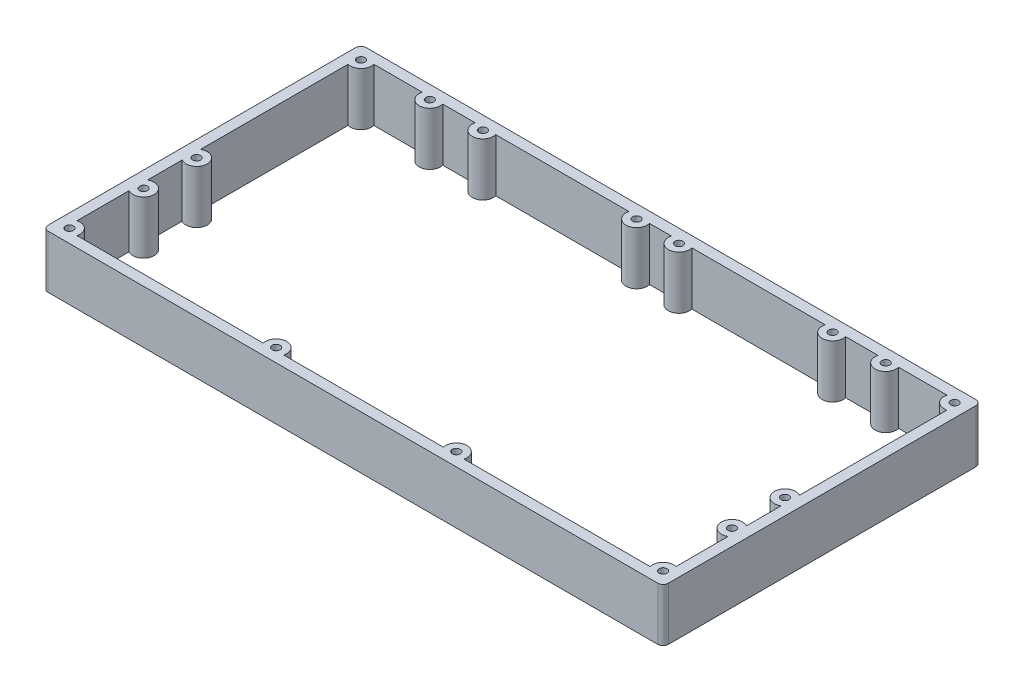
SolidWorks part; units mm, degrees
ref_plane "前视基准面" through (0, 0, 0) normal (0, 0, 1) x (1, 0, 0)
ref_plane "上视基准面" through (0, 0, 0) normal (0, 1, 0) x (1, 0, 0)
ref_plane "右视基准面" through (0, 0, 0) normal (1, 0, 0) x (0, 0, -1)
sketch "草图1" plane through (0, 0, 0) normal (0, 1, 0) x (1, 0, 0)
  line L0 (-13.5, 0) -> (0, 0) construction
  line L1 (-117, 60) -> (117, 60)
  line L2 (-117, 60) -> (-117, -60)
  line L3 (-117, -60) -> (117, -60)
  line L4 (117, 60) -> (117, -60)
  line L5 (-117, 60) -> (117, -60) construction
  line L6 (-117, -60) -> (117, 60) construction
  line L7 (0, 0) -> (0, 78.7988) construction
  circle A0 centre (-58.5, 0) radius 45
  circle A1 centre (58.5, 0) radius 45
  point P0 (0, 0)
  dimension "D3" = 90
  dimension "D4" = 13.5
  dimension "D1" = 234
  dimension "D2" = 120
extrude "凸台-拉伸1" add sketch "草图1" along normal blind 3
sketch "草图2" plane through (0, 3, 0) normal (0, 1, 0) x (1, 0, 0)
  line L0 (-58.5, 0) -> (-58.5, 18.4943) construction
  line L1 (0, 0) -> (0, 13.9098) construction
  circle A8 centre (-58.5, 0) radius 50 construction
  circle A9 centre (-88.5, -40) radius 1.5
  circle A10 centre (-83.5, 43.3013) radius 1.5
  circle A11 centre (-33.5, 43.3013) radius 1.5
  circle A12 centre (-28.5, -40) radius 1.5
  circle A13 centre (28.5, -40) radius 1.5
  circle A14 centre (88.5, -40) radius 1.5
  circle A15 centre (33.5, 43.3013) radius 1.5
  circle A16 centre (83.5, 43.3013) radius 1.5
  dimension "D1" = 100
  dimension "D3" = 30
  dimension "D2" = 3
  dimension "D4" = 25
  dimension "D5" = 3
extrude "切除-拉伸1" cut sketch "草图2" against normal blind 3
sketch "草图3" plane through (0, 3, 0) normal (0, 1, 0) x (1, 0, 0)
  line L0 (-117, 60) -> (-117, -60) construction
  line L1 (-117, -60) -> (117, -60) construction
  line L2 (0, 0) -> (0, -72.8657) construction
  line L3 (117, 60) -> (-117, 60) construction
  circle A0 centre (-111, -28) radius 1.5
  circle A1 centre (-111, -8) radius 1.5
  circle A2 centre (111, -8) radius 1.5
  circle A3 centre (111, -28) radius 1.5
  circle A4 centre (-86, 55) radius 1.5
  circle A5 centre (-66, 55) radius 1.5
  circle A6 centre (66, 55) radius 1.5
  circle A7 centre (86, 55) radius 1.5
  dimension "D1" = 3
  dimension "D2" = 6
  dimension "D3" = 32
  dimension "D4" = 3
  dimension "D5" = 20
  dimension "D6" = 3
  dimension "D7" = 5
  dimension "D8" = 31
  dimension "D9" = 3
  dimension "D10" = 20
extrude "切除-拉伸2" cut sketch "草图3" against normal blind 3
sketch "草图4" plane through (0, 3, 0) normal (0, 1, 0) x (1, 0, 0)
  line L0 (-117, 60) -> (-117, -60) construction
  line L1 (-117, -60) -> (117, -60) construction
  line L2 (117, 60) -> (-117, 60) construction
  line L3 (117, -60) -> (117, 60) construction
  circle A0 centre (-112, -55) radius 1.5
  circle A1 centre (-112, 55) radius 1.5
  circle A2 centre (112, 55) radius 1.5
  circle A3 centre (112, -55) radius 1.5
  circle A4 centre (-34, -55) radius 1.5
  circle A5 centre (34, -55) radius 1.5
  dimension "D1" = 3
  dimension "D2" = 5
  dimension "D3" = 5
  dimension "D4" = 3
  dimension "D5" = 5
  dimension "D6" = 5
  dimension "D7" = 3
  dimension "D8" = 5
  dimension "D9" = 5
  dimension "D10" = 3
  dimension "D11" = 3
  dimension "D12" = 78
  dimension "D13" = 3
  dimension "D14" = 78
  dimension "D15" = 5
  dimension "D16" = 5
  dimension "D17" = 5
  dimension "D18" = 5
extrude "切除-拉伸3" cut sketch "草图4" against normal blind 3
sketch "草图5" plane through (0, 3, 0) normal (0, 1, 0) x (1, 0, 0)
  line L0 (117, 60) -> (-117, 60) construction
  circle A0 centre (-8, 55) radius 1.5
  circle A1 centre (8, 55) radius 1.5
  dimension "D1" = 3
  dimension "D2" = 5
  dimension "D3" = 8
  dimension "D4" = 3
  dimension "D5" = 5
  dimension "D6" = 8
extrude "切除-拉伸4" cut sketch "草图5" against normal blind 3
fillet "圆角1" radius 2 4 edges at (-117, 1.5, -60) (-117, 1.5, 60) (117, 1.5, 60) (117, 1.5, -60)
sketch "草图6" plane through (0, 3, 0) normal (0, 1, 0) x (1, 0, 0)
  line L5 (109.5, -12.7697) -> (109.5, -23.2303)
  line L6 (-107.6699, 52.5) -> (-90.3301, 52.5)
  line L7 (-109.5, 50.6699) -> (-109.5, -3.2303)
  line L12 (-107.6699, -52.5) -> (-38.3301, -52.5)
  line L13 (109.5, 50.6699) -> (109.5, -3.2303)
  line L14 (-108.1247, 51.8406) -> (108.1247, -51.8406) construction
  line L15 (-108.1247, -51.8406) -> (108.1247, 51.8406) construction
  line L16 (109.5, -32.7697) -> (109.5, -50.6699)
  line L17 (90.3301, 52.5) -> (107.6699, 52.5)
  line L18 (70.3301, 52.5) -> (81.6699, 52.5)
  line L19 (12.3301, 52.5) -> (61.6699, 52.5)
  line L20 (-3.6699, 52.5) -> (3.6699, 52.5)
  line L21 (-81.6699, 52.5) -> (-70.3301, 52.5)
  line L22 (-61.6699, 52.5) -> (-12.3301, 52.5)
  line L23 (-109.5, -12.7697) -> (-109.5, -23.2303)
  line L24 (-109.5, -32.7697) -> (-109.5, -50.6699)
  line L25 (-29.6699, -52.5) -> (29.6699, -52.5)
  line L26 (38.3301, -52.5) -> (107.6699, -52.5)
  arc A12 (-109.5, -12.7697) -> (-109.5, -3.2303) centre (-111, -8) ccw
  arc A13 (-109.5, -32.7697) -> (-109.5, -23.2303) centre (-111, -28) ccw
  arc A14 (-109.5, 50.6699) -> (-107.6699, 52.5) centre (-112, 55) ccw
  arc A15 (-90.3301, 52.5) -> (-81.6699, 52.5) centre (-86, 55) ccw
  arc A16 (-70.3301, 52.5) -> (-61.6699, 52.5) centre (-66, 55) ccw
  arc A17 (-12.3301, 52.5) -> (-3.6699, 52.5) centre (-8, 55) ccw
  arc A18 (3.6699, 52.5) -> (12.3301, 52.5) centre (8, 55) ccw
  arc A19 (61.6699, 52.5) -> (70.3301, 52.5) centre (66, 55) ccw
  arc A20 (81.6699, 52.5) -> (90.3301, 52.5) centre (86, 55) ccw
  arc A21 (107.6699, 52.5) -> (109.5, 50.6699) centre (112, 55) ccw
  arc A22 (109.5, -3.2303) -> (109.5, -12.7697) centre (111, -8) ccw
  arc A23 (109.5, -23.2303) -> (109.5, -32.7697) centre (111, -28) ccw
  arc A24 (109.5, -50.6699) -> (107.6699, -52.5) centre (112, -55) ccw
  arc A25 (38.3301, -52.5) -> (29.6699, -52.5) centre (34, -55) ccw
  arc A26 (-29.6699, -52.5) -> (-38.3301, -52.5) centre (-34, -55) ccw
  arc A27 (-107.6699, -52.5) -> (-109.5, -50.6699) centre (-112, -55) ccw
  point P0 (0, 0)
  dimension "D3" = 10
  dimension "D4" = 10
  dimension "D5" = 10
  dimension "D6" = 10
  dimension "D7" = 10
  dimension "D8" = 10
  dimension "D9" = 10
  dimension "D10" = 10
  dimension "D11" = 10
  dimension "D12" = 10
  dimension "D13" = 10
  dimension "D14" = 10
  dimension "D15" = 10
  dimension "D16" = 10
  dimension "D17" = 10
  dimension "D18" = 10
extrude "切除-拉伸5" cut sketch "草图6" against normal blind 10
sketch "草图7" plane through (0, 3, 0) normal (0, 1, 0) x (1, 0, 0)
  line L0 (-90.3301, 52.5) -> (-107.6699, 52.5) construction
  line L1 (-70.3301, 52.5) -> (-81.6699, 52.5) construction
  line L2 (-12.3301, 52.5) -> (-61.6699, 52.5) construction
  line L3 (-109.5, 50.6699) -> (-109.5, -3.2303) construction
  line L4 (-117, 58) -> (-117, -58)
  line L5 (-115, -60) -> (115, -60)
  line L6 (117, -58) -> (117, 58)
  line L7 (115, 60) -> (-115, 60)
  line L8 (-117, 58) -> (-117, -58)
  line L9 (-115, -60) -> (115, -60)
  line L10 (117, -58) -> (117, 58)
  line L11 (115, 60) -> (-115, 60)
  line L12 (-109.5, -12.7697) -> (-109.5, -23.2303) construction
  line L13 (-109.5, -32.7697) -> (-109.5, -50.6699) construction
  line L14 (-107.6699, -52.5) -> (-38.3301, -52.5) construction
  line L15 (-29.6699, -52.5) -> (29.6699, -52.5) construction
  line L16 (38.3301, -52.5) -> (107.6699, -52.5) construction
  line L17 (3.6699, 52.5) -> (-3.6699, 52.5) construction
  line L18 (61.6699, 52.5) -> (12.3301, 52.5) construction
  line L19 (81.6699, 52.5) -> (70.3301, 52.5) construction
  line L20 (107.6699, 52.5) -> (90.3301, 52.5) construction
  line L21 (109.5, -3.2303) -> (109.5, 50.6699) construction
  line L22 (109.5, -23.2303) -> (109.5, -12.7697) construction
  line L23 (109.5, -50.6699) -> (109.5, -32.7697) construction
  line L24 (109.5, -50.6699) -> (109.5, -32.7697)
  line L25 (109.5, -23.2303) -> (109.5, -12.7697)
  line L26 (109.5, -3.2303) -> (109.5, 50.6699)
  line L27 (107.6699, 52.5) -> (90.3301, 52.5)
  line L28 (81.6699, 52.5) -> (70.3301, 52.5)
  line L29 (61.6699, 52.5) -> (12.3301, 52.5)
  line L30 (3.6699, 52.5) -> (-3.6699, 52.5)
  line L31 (38.3301, -52.5) -> (107.6699, -52.5)
  line L32 (-29.6699, -52.5) -> (29.6699, -52.5)
  line L33 (-107.6699, -52.5) -> (-38.3301, -52.5)
  line L34 (-109.5, -32.7697) -> (-109.5, -50.6699)
  line L35 (-109.5, -12.7697) -> (-109.5, -23.2303)
  line L36 (-109.5, 50.6699) -> (-109.5, -3.2303)
  line L37 (-12.3301, 52.5) -> (-61.6699, 52.5)
  line L38 (-70.3301, 52.5) -> (-81.6699, 52.5)
  line L39 (-90.3301, 52.5) -> (-107.6699, 52.5)
  circle A0 centre (-112, 55) radius 1.5 construction
  circle A1 centre (-111, -8) radius 1.5 construction
  circle A2 centre (-111, -28) radius 1.5 construction
  circle A3 centre (-112, -55) radius 1.5 construction
  arc A4 (-117, -58) -> (-115, -60) centre (-115, -58) ccw
  arc A5 (115, -60) -> (117, -58) centre (115, -58) ccw
  arc A6 (117, 58) -> (115, 60) centre (115, 58) ccw
  arc A7 (-115, 60) -> (-117, 58) centre (-115, 58) ccw
  arc A8 (-117, -58) -> (-115, -60) centre (-115, -58) ccw
  arc A9 (115, -60) -> (117, -58) centre (115, -58) ccw
  arc A10 (117, 58) -> (115, 60) centre (115, 58) ccw
  arc A11 (-115, 60) -> (-117, 58) centre (-115, 58) ccw
  arc A12 (-109.5, 50.6699) -> (-107.6699, 52.5) centre (-112, 55) ccw construction
  arc A13 (-90.3301, 52.5) -> (-81.6699, 52.5) centre (-86, 55) ccw construction
  circle A14 centre (-86, 55) radius 1.5 construction
  circle A15 centre (-66, 55) radius 1.5 construction
  circle A16 centre (-8, 55) radius 1.5 construction
  circle A17 centre (8, 55) radius 1.5 construction
  circle A18 centre (66, 55) radius 1.5 construction
  circle A19 centre (86, 55) radius 1.5 construction
  arc A20 (-70.3301, 52.5) -> (-61.6699, 52.5) centre (-66, 55) ccw construction
  arc A21 (-109.5, -12.7697) -> (-109.5, -3.2303) centre (-111, -8) ccw construction
  arc A22 (-109.5, -32.7697) -> (-109.5, -23.2303) centre (-111, -28) ccw construction
  arc A23 (-107.6699, -52.5) -> (-109.5, -50.6699) centre (-112, -55) ccw construction
  circle A24 centre (-34, -55) radius 1.5 construction
  arc A25 (-29.6699, -52.5) -> (-38.3301, -52.5) centre (-34, -55) ccw construction
  arc A26 (38.3301, -52.5) -> (29.6699, -52.5) centre (34, -55) ccw construction
  circle A27 centre (34, -55) radius 1.5 construction
  arc A28 (-12.3301, 52.5) -> (-3.6699, 52.5) centre (-8, 55) ccw construction
  arc A29 (3.6699, 52.5) -> (12.3301, 52.5) centre (8, 55) ccw construction
  arc A30 (61.6699, 52.5) -> (70.3301, 52.5) centre (66, 55) ccw construction
  arc A31 (81.6699, 52.5) -> (90.3301, 52.5) centre (86, 55) ccw construction
  arc A32 (107.6699, 52.5) -> (109.5, 50.6699) centre (112, 55) ccw construction
  circle A33 centre (112, 55) radius 1.5 construction
  arc A34 (109.5, -3.2303) -> (109.5, -12.7697) centre (111, -8) ccw construction
  circle A35 centre (111, -8) radius 1.5 construction
  arc A36 (109.5, -23.2303) -> (109.5, -32.7697) centre (111, -28) ccw construction
  circle A37 centre (111, -28) radius 1.5 construction
  arc A38 (109.5, -50.6699) -> (107.6699, -52.5) centre (112, -55) ccw construction
  circle A39 centre (112, -55) radius 1.5 construction
  circle A40 centre (112, -55) radius 1.5
  arc A41 (109.5, -50.6699) -> (107.6699, -52.5) centre (112, -55) ccw
  circle A42 centre (111, -28) radius 1.5
  arc A43 (109.5, -23.2303) -> (109.5, -32.7697) centre (111, -28) ccw
  circle A44 centre (111, -8) radius 1.5
  arc A45 (109.5, -3.2303) -> (109.5, -12.7697) centre (111, -8) ccw
  circle A46 centre (112, 55) radius 1.5
  arc A47 (107.6699, 52.5) -> (109.5, 50.6699) centre (112, 55) ccw
  arc A48 (81.6699, 52.5) -> (90.3301, 52.5) centre (86, 55) ccw
  arc A49 (61.6699, 52.5) -> (70.3301, 52.5) centre (66, 55) ccw
  arc A50 (3.6699, 52.5) -> (12.3301, 52.5) centre (8, 55) ccw
  arc A51 (-12.3301, 52.5) -> (-3.6699, 52.5) centre (-8, 55) ccw
  circle A52 centre (34, -55) radius 1.5
  arc A53 (38.3301, -52.5) -> (29.6699, -52.5) centre (34, -55) ccw
  arc A54 (-29.6699, -52.5) -> (-38.3301, -52.5) centre (-34, -55) ccw
  circle A55 centre (-34, -55) radius 1.5
  arc A56 (-107.6699, -52.5) -> (-109.5, -50.6699) centre (-112, -55) ccw
  arc A57 (-109.5, -32.7697) -> (-109.5, -23.2303) centre (-111, -28) ccw
  arc A58 (-109.5, -12.7697) -> (-109.5, -3.2303) centre (-111, -8) ccw
  arc A59 (-70.3301, 52.5) -> (-61.6699, 52.5) centre (-66, 55) ccw
  circle A60 centre (86, 55) radius 1.5
  circle A61 centre (66, 55) radius 1.5
  circle A62 centre (8, 55) radius 1.5
  circle A63 centre (-8, 55) radius 1.5
  circle A64 centre (-66, 55) radius 1.5
  circle A65 centre (-86, 55) radius 1.5
  arc A66 (-90.3301, 52.5) -> (-81.6699, 52.5) centre (-86, 55) ccw
  arc A67 (-109.5, 50.6699) -> (-107.6699, 52.5) centre (-112, 55) ccw
  circle A68 centre (-112, 55) radius 1.5
  circle A69 centre (-112, -55) radius 1.5
  circle A70 centre (-111, -28) radius 1.5
  circle A71 centre (-111, -8) radius 1.5
  dimension "D1" = 0
extrude "凸台-拉伸2" add sketch "草图7" along normal blind 17
sketch "草图8" plane through (0, 20, 0) normal (0, 1, 0) x (1, 0, 0)
  line L0 (-90, 55) -> (-108, 55)
  line L1 (108, -55) -> (38, -55)
  line L2 (112, -51) -> (112, -31.873)
  line L3 (108, 55) -> (90, 55)
  line L4 (-112, -51) -> (-112, -31.873)
  line L5 (108.4096, -53.2368) -> (-108.4096, 53.2368) construction
  line L6 (108.4096, 53.2368) -> (-108.4096, -53.2368) construction
  line L7 (-70, 55) -> (-82, 55)
  line L8 (-12, 55) -> (-62, 55)
  line L9 (4, 55) -> (-4, 55)
  line L10 (62, 55) -> (12, 55)
  line L11 (82, 55) -> (70, 55)
  line L12 (112, -4.127) -> (112, 51)
  line L13 (112, -24.127) -> (112, -11.873)
  line L14 (30, -55) -> (-30, -55)
  line L15 (-38, -55) -> (-108, -55)
  line L16 (-112, -24.127) -> (-112, -11.873)
  line L17 (-112, -4.127) -> (-112, 51)
  arc A0 (-112, -11.873) -> (-112, -4.127) centre (-111, -8) ccw
  arc A1 (-112, -31.873) -> (-112, -24.127) centre (-111, -28) ccw
  arc A2 (-108, -55) -> (-112, -51) centre (-112, -55) ccw
  arc A3 (-30, -55) -> (-38, -55) centre (-34, -55) ccw
  arc A4 (-112, 51) -> (-108, 55) centre (-112, 55) ccw
  arc A5 (-90, 55) -> (-82, 55) centre (-86, 55) ccw
  arc A6 (-70, 55) -> (-62, 55) centre (-66, 55) ccw
  arc A7 (-12, 55) -> (-4, 55) centre (-8, 55) ccw
  arc A8 (4, 55) -> (12, 55) centre (8, 55) ccw
  arc A9 (62, 55) -> (70, 55) centre (66, 55) ccw
  arc A10 (82, 55) -> (90, 55) centre (86, 55) ccw
  arc A11 (108, 55) -> (112, 51) centre (112, 55) ccw
  arc A12 (112, -4.127) -> (112, -11.873) centre (111, -8) ccw
  arc A13 (112, -24.127) -> (112, -31.873) centre (111, -28) ccw
  arc A14 (112, -51) -> (108, -55) centre (112, -55) ccw
  arc A15 (38, -55) -> (30, -55) centre (34, -55) ccw
  point P48 (0, 0)
  dimension "D1" = 8
  dimension "D2" = 8
  dimension "D3" = 8
  dimension "D4" = 8
  dimension "D5" = 8
  dimension "D6" = 8
  dimension "D7" = 8
  dimension "D8" = 8
  dimension "D9" = 8
  dimension "D10" = 8
  dimension "D11" = 8
  dimension "D12" = 8
  dimension "D13" = 8
  dimension "D14" = 8
  dimension "D15" = 8
  dimension "D16" = 8
extrude "切除-拉伸6" cut sketch "草图8" against normal blind 50
sketch "草图9" plane through (0, 20, 0) normal (0, 1, 0) x (1, 0, 0)
  line L0 (113, 51.127) -> (113, -4.5359)
  line L5 (108.4096, 53.2368) -> (-112, -55) construction
  line L6 (108.4096, -53.2368) -> (-108.4096, 53.2368) construction
  line L7 (108.127, -56) -> (37.873, -56)
  line L8 (-113, 51.127) -> (-113, -4.5359)
  line L9 (108.127, 56) -> (89.873, 56)
  line L10 (-89.873, 56) -> (-108.127, 56)
  line L11 (-69.873, 56) -> (-82.127, 56)
  line L12 (4.127, 56) -> (-4.127, 56)
  line L13 (-11.873, 56) -> (-62.127, 56)
  line L14 (62.127, 56) -> (11.873, 56)
  line L15 (82.127, 56) -> (69.873, 56)
  line L16 (113, -31.4641) -> (113, -51.127)
  line L17 (113, -11.4641) -> (113, -24.5359)
  line L18 (-37.873, -56) -> (-108.127, -56)
  line L19 (30.127, -56) -> (-30.127, -56)
  line L20 (-113, -31.4641) -> (-113, -51.127)
  line L21 (-113, -11.4641) -> (-113, -24.5359)
  arc A0 (-113, 51.127) -> (-108.127, 56) centre (-112, 55) ccw
  arc A1 (-89.873, 56) -> (-82.127, 56) centre (-86, 55) ccw
  arc A2 (-69.873, 56) -> (-62.127, 56) centre (-66, 55) ccw
  arc A3 (-11.873, 56) -> (-4.127, 56) centre (-8, 55) ccw
  arc A4 (4.127, 56) -> (11.873, 56) centre (8, 55) ccw
  arc A5 (62.127, 56) -> (69.873, 56) centre (66, 55) ccw
  arc A6 (82.127, 56) -> (89.873, 56) centre (86, 55) ccw
  arc A7 (108.127, 56) -> (113, 51.127) centre (112, 55) ccw
  arc A8 (113, -4.5359) -> (113, -11.4641) centre (111, -8) ccw
  arc A9 (113, -24.5359) -> (113, -31.4641) centre (111, -28) ccw
  arc A10 (113, -51.127) -> (108.127, -56) centre (112, -55) ccw
  arc A11 (37.873, -56) -> (30.127, -56) centre (34, -55) ccw
  arc A12 (-108.127, -56) -> (-113, -51.127) centre (-112, -55) ccw
  arc A13 (-30.127, -56) -> (-37.873, -56) centre (-34, -55) ccw
  arc A14 (-113, -31.4641) -> (-113, -24.5359) centre (-111, -28) ccw
  arc A15 (-113, -11.4641) -> (-113, -4.5359) centre (-111, -8) ccw
  point P48 (0, 0)
extrude "切除-拉伸7" cut sketch "草图9" against normal blind 73
